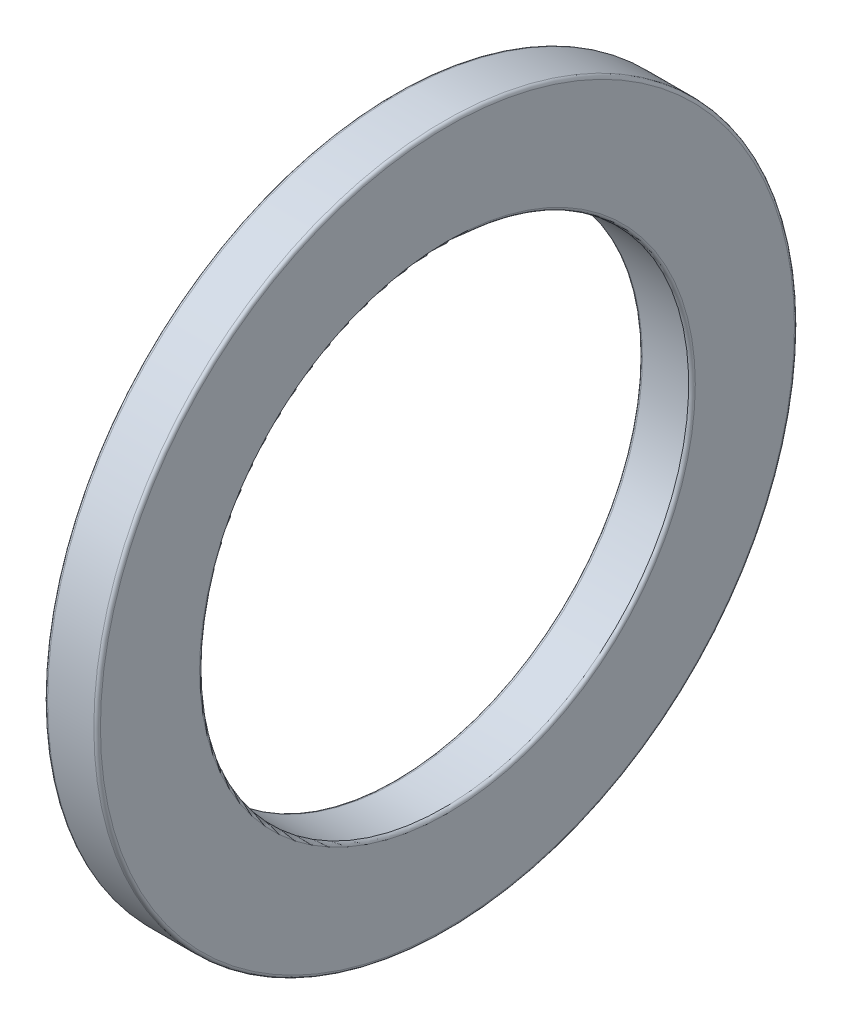
SolidWorks part; units mm, degrees
ref_plane "Спереди" through (0, 0, 0) normal (0, 0, 1) x (1, 0, 0)
ref_plane "Сверху" through (0, 0, 0) normal (0, 1, 0) x (1, 0, 0)
ref_plane "Справа" through (0, 0, 0) normal (1, 0, 0) x (0, 0, -1)
sketch "Эскиз1" plane through (0, 0, 0) normal (0, 0, 1) x (1, 0, 0)
  line L0 (0, 0) -> (32.9731, 0) construction
  line L1 (0, 37) -> (8, 37)
  line L2 (8, 37) -> (8, 53)
  line L3 (8, 53) -> (0, 53)
  line L4 (0, 53) -> (0, 48.4641)
  line L5 (0, 41.5359) -> (0, 37)
  arc A1 (0, 41.5359) -> (0, 48.4641) centre (-0.5, 45) ccw
  dimension "D3" = 45
  dimension "D6" = 7
  dimension "D1" = 37
  dimension "D2" = 53
  dimension "D4" = 0.5
  dimension "D5" = 8
revolve "Повернуть1" add sketch "Эскиз1" angle 360 about L0
fillet "Скругление1" radius 0.5 4 edges at (0, 0, 37) (0, 0, 53) (8, 0, 37) (8, 0, 53)
